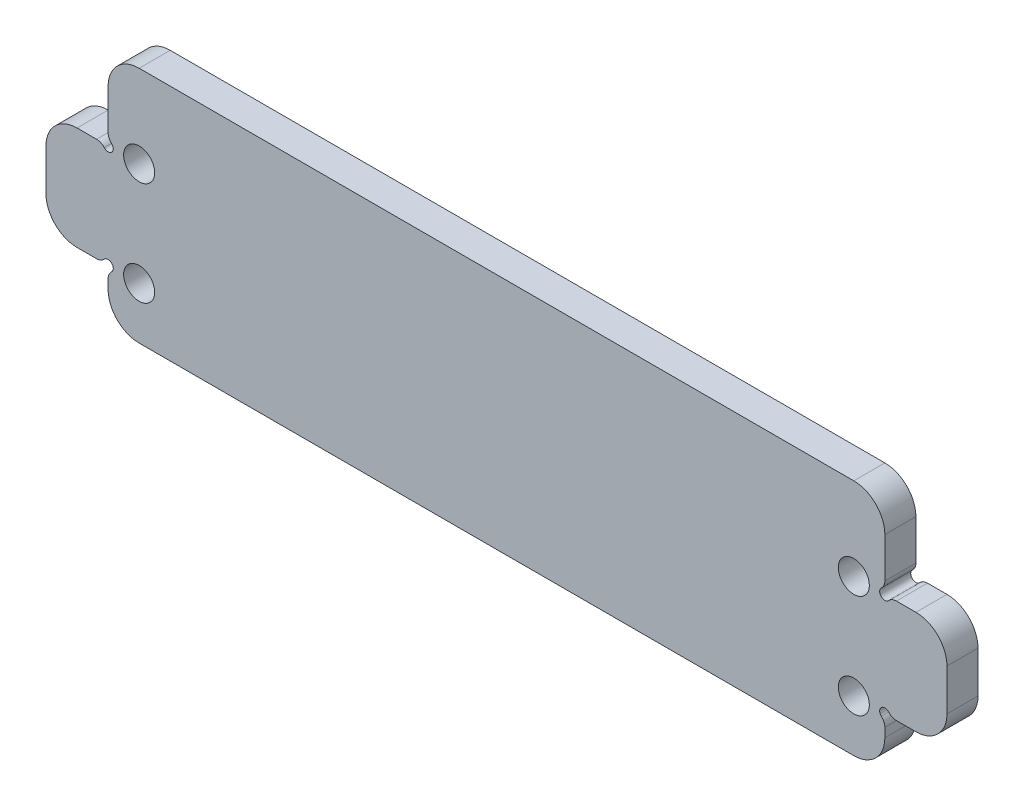
SolidWorks part; units mm, degrees
material "Thornel Mat VMA"
ref_plane "前视基准面" through (0, 0, 0) normal (0, 0, 1) x (1, 0, 0)
ref_plane "上视基准面" through (0, 0, 0) normal (0, 1, 0) x (1, 0, 0)
ref_plane "右视基准面" through (0, 0, 0) normal (1, 0, 0) x (0, 0, -1)
other "Configuration Table"
sketch "草图1" plane through (0, 0, 0) normal (0, 0, 1) x (1, 0, 0)
  line L1 (-37.525, 11.5) -> (37.525, 11.5)
  line L2 (-37.525, 11.5) -> (-37.525, 4)
  line L3 (-37.525, -11.5) -> (37.525, -11.5)
  line L4 (37.525, 11.5) -> (37.525, 4)
  line L5 (-37.525, 11.5) -> (37.525, -11.5) construction
  line L6 (-37.525, -11.5) -> (37.525, 11.5) construction
  line L7 (43.525, -6.5) -> (38.025, -6.5)
  line L8 (43.525, -6.5) -> (43.525, 3.5)
  line L9 (43.525, 3.5) -> (38.025, 3.5)
  line L11 (43.525, -6.5) -> (37.7822, 3.0713) construction
  line L12 (43.525, 3.5) -> (37.7822, -6.0713) construction
  line L13 (37.525, -7) -> (37.525, -11.5)
  line L14 (0, 0) -> (0, -6.0713) construction
  line L15 (-43.525, -6.5) -> (-43.525, 3.5)
  line L16 (-43.525, -6.5) -> (-38.025, -6.5)
  line L17 (-43.525, 3.5) -> (-38.025, 3.5)
  line L18 (-37.525, -7) -> (-37.525, -11.5)
  circle A0 centre (34.525, 3.5) radius 1.5
  circle A1 centre (34.525, -6.5) radius 1.5
  arc A2 (37.525, 4) -> (38.025, 3.5) centre (37.525, 3.5) ccw
  arc A3 (38.025, -6.5) -> (37.525, -7) centre (37.525, -6.5) ccw
  arc A4 (-38.025, -6.5) -> (-37.525, -7) centre (-37.525, -6.5) cw
  arc A5 (-37.525, 4) -> (-38.025, 3.5) centre (-37.525, 3.5) cw
  circle A6 centre (-34.525, -6.5) radius 1.5
  circle A7 centre (-34.525, 3.5) radius 1.5
  point P0 (0, 0)
  point P10 (40.525, -1.5)
  dimension "D6" = 10
  dimension "D7" = 5
  dimension "D8" = 3
  dimension "D9" = 3
  dimension "D10" = 1
  dimension "D11" = 1
  dimension "D12" = 3
  dimension "D1" = 75.05
  dimension "D2" = 23
  dimension "D3" = 6
  dimension "D4" = 10
  dimension "D5" = 5
extrude "凸台-拉伸1" add sketch "草图1" along normal blind 3
fillet "圆角1" radius 3 8 edges at (37.525, -11.5, 1.5) (-37.525, -11.5, 1.5) (-43.525, -6.5, 1.5) (37.525, 11.5, 1.5) (43.525, 3.5, 1.5) (43.525, -6.5, 1.5) (-43.525, 3.5, 1.5) (-37.525, 11.5, 1.5)
fillet "圆角2" radius 1 8 edges at (-37.525, -7, 1.5) (37.525, 4, 1.5) (38.025, 3.5, 1.5) (38.025, -6.5, 1.5) (37.525, -7, 1.5) (-38.025, -6.5, 1.5) (-38.025, 3.5, 1.5) (-37.525, 4, 1.5)
